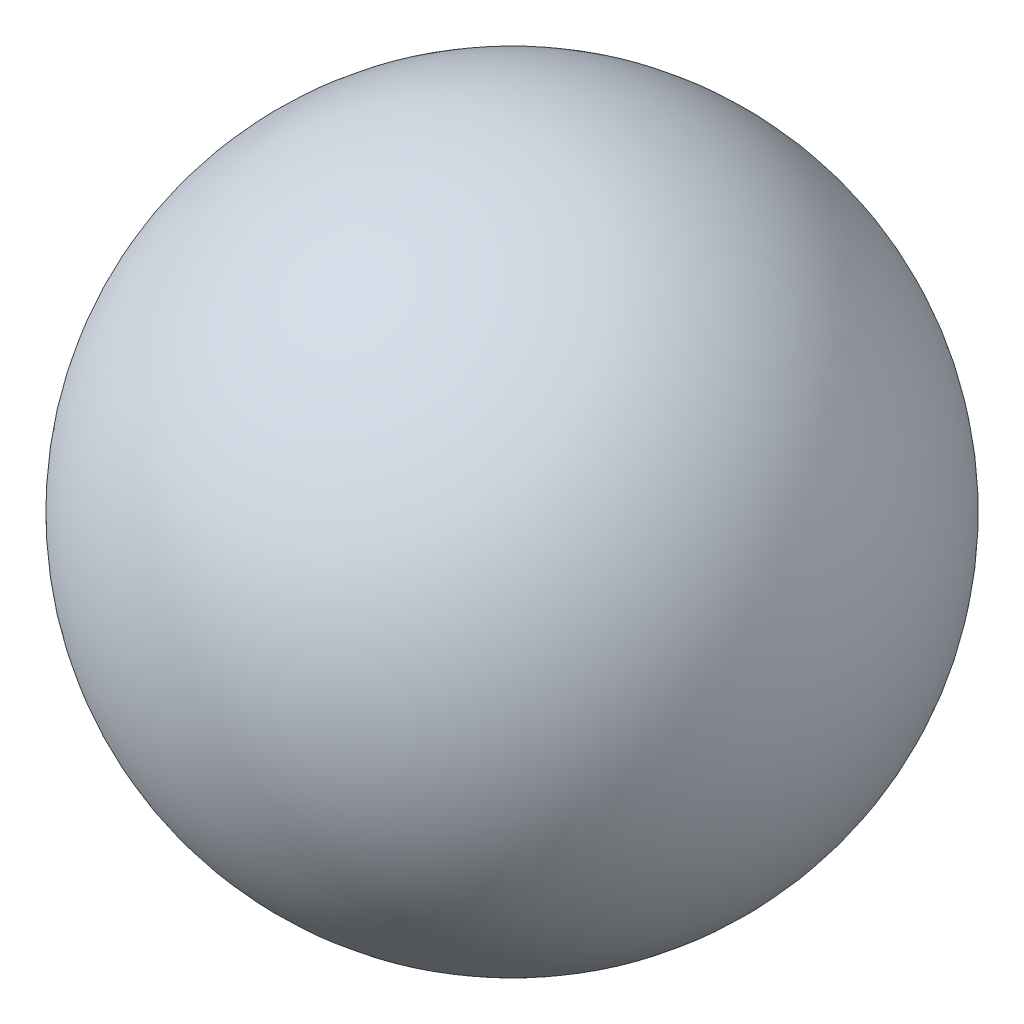
SolidWorks part; units mm, degrees
ref_plane "Alzado" through (0, 0, 0) normal (0, 0, 1) x (1, 0, 0)
ref_plane "Planta" through (0, 0, 0) normal (0, 1, 0) x (1, 0, 0)
ref_plane "Vista lateral" through (0, 0, 0) normal (1, 0, 0) x (0, 0, -1)
sketch "Croquis1" plane through (0, 0, 0) normal (0, 0, 1) x (1, 0, 0)
  line L0 (0, 4) -> (0, -4) construction
  line L1 (0, 4) -> (0, -4)
  arc A0 (0, 4) -> (0, -4) centre (0, 0) cw
  dimension "D1" = 4
revolve "Revolución4" add sketch "Croquis1" angle 360 about L0
